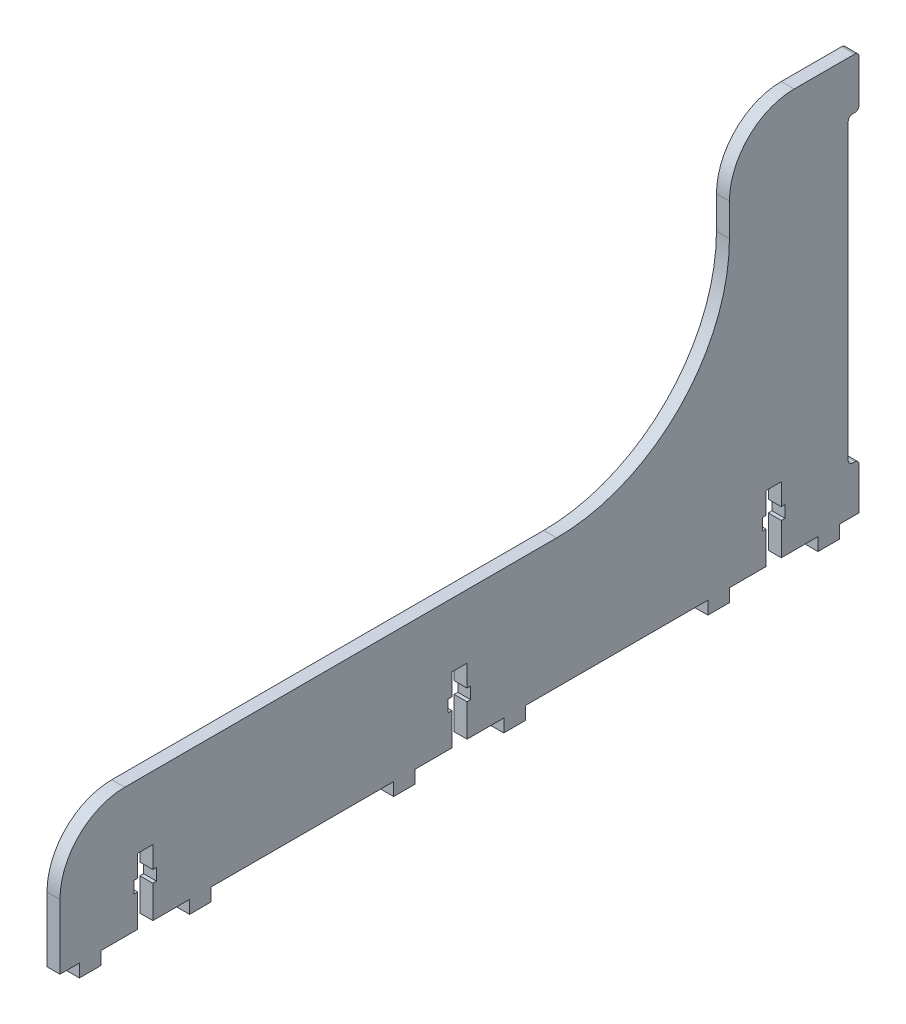
SolidWorks part; units mm, degrees
ref_plane "Front Plane" through (0, 0, 0) normal (0, 0, 1) x (1, 0, 0)
ref_plane "Top Plane" through (0, 0, 0) normal (0, 1, 0) x (1, 0, 0)
ref_plane "Right Plane" through (0, 0, 0) normal (1, 0, 0) x (0, 0, -1)
sketch "Sketch1" plane through (0, 0, 0) normal (1, 0, 0) x (0, 0, -1)
  line L0 (-185, -92.5) -> (185, 92.5) construction
  line L1 (183, 92.5) -> (155, 92.5)
  line L2 (-185, -92.5) -> (-185, -62.5)
  line L3 (-185, -92.5) -> (-176, -92.5)
  line L4 (185, -92.5) -> (185, -73)
  line L5 (0, -32.5) -> (0, -92.5) construction
  line L6 (149, -92.5) -> (149, -77.5)
  line L7 (149, -77.5) -> (150.7, -77.5)
  line L8 (150.7, -77.5) -> (150.7, -72)
  line L9 (150.7, -72) -> (149, -72)
  line L10 (149, -72) -> (149, -62)
  line L11 (149, -62) -> (142, -62)
  line L12 (142, -62) -> (142, -72)
  line L13 (142, -72) -> (140.3, -72)
  line L14 (140.3, -72) -> (140.3, -77.5)
  line L15 (140.3, -77.5) -> (142, -77.5)
  line L16 (142, -77.5) -> (142, -92.5)
  line L17 (166, -92.5) -> (166, -98.5)
  line L18 (166, -98.5) -> (176, -98.5)
  line L19 (176, -98.5) -> (176, -92.5)
  line L20 (115, -92.5) -> (115, -98.5)
  line L21 (115, -98.5) -> (125, -98.5)
  line L22 (125, -98.5) -> (125, -92.5)
  line L23 (30.5, -92.5) -> (30.5, -98.5)
  line L24 (30.5, -98.5) -> (20.5, -98.5)
  line L25 (20.5, -98.5) -> (20.5, -92.5)
  line L26 (-20.5, -92.5) -> (-20.5, -98.5)
  line L27 (-20.5, -98.5) -> (-30.5, -98.5)
  line L28 (-30.5, -98.5) -> (-30.5, -92.5)
  line L29 (-115, -92.5) -> (-115, -98.5)
  line L30 (-115, -98.5) -> (-125, -98.5)
  line L31 (-125, -98.5) -> (-125, -92.5)
  line L32 (-176, -92.5) -> (-176, -98.5)
  line L33 (-176, -98.5) -> (-166, -98.5)
  line L34 (-166, -98.5) -> (-166, -92.5)
  line L35 (166, -95.5) -> (125, -95.5) construction
  line L36 (115, -95.5) -> (30.5, -95.5) construction
  line L37 (20.5, -95.5) -> (-20.5, -95.5) construction
  line L38 (-30.5, -95.5) -> (-115, -95.5) construction
  line L39 (-125, -95.5) -> (-166, -95.5) construction
  line L40 (-166, -92.5) -> (-125, -92.5)
  line L41 (-115, -92.5) -> (-30.5, -92.5)
  line L42 (-20.5, -92.5) -> (20.5, -92.5)
  line L43 (30.5, -92.5) -> (115, -92.5)
  line L44 (125, -92.5) -> (166, -92.5)
  line L45 (145.5, -62) -> (145.5, -92.5) construction
  line L46 (176, -92.5) -> (185, -92.5)
  line L47 (72.75, -92.5) -> (72.75, -27.5329) construction
  line L48 (-3.5, -92.5) -> (-3.5, -77.5)
  line L49 (-3.5, -77.5) -> (-5.2, -77.5)
  line L50 (-5.2, -77.5) -> (-5.2, -72)
  line L51 (-5.2, -72) -> (-3.5, -72)
  line L52 (-3.5, -72) -> (-3.5, -62)
  line L53 (-3.5, -62) -> (3.5, -62)
  line L54 (3.5, -62) -> (3.5, -72)
  line L55 (3.5, -72) -> (5.2, -72)
  line L56 (5.2, -72) -> (5.2, -77.5)
  line L57 (5.2, -77.5) -> (3.5, -77.5)
  line L58 (3.5, -77.5) -> (3.5, -92.5)
  line L59 (-149, -92.5) -> (-149, -77.5)
  line L60 (-149, -77.5) -> (-150.7, -77.5)
  line L61 (-150.7, -77.5) -> (-150.7, -72)
  line L62 (-150.7, -72) -> (-149, -72)
  line L63 (-149, -72) -> (-149, -62)
  line L64 (-149, -62) -> (-142, -62)
  line L65 (-142, -62) -> (-142, -72)
  line L66 (-142, -72) -> (-140.3, -72)
  line L67 (-140.3, -72) -> (-140.3, -77.5)
  line L68 (-142, -77.5) -> (-142, -92.5)
  line L69 (-140.3, -77.5) -> (-142, -77.5)
  line L70 (183, -71) -> (182, -71)
  line L71 (-155, -32.5) -> (45, -32.5)
  line L72 (125, 47.5) -> (125, 62.5)
  line L73 (180, -69) -> (180, 67)
  line L74 (182, 69) -> (183, 69)
  line L75 (185, 71) -> (185, 90.5)
  arc A0 (125, 47.5) -> (45, -32.5) centre (45, 47.5) cw
  arc A1 (155, 92.5) -> (125, 62.5) centre (155, 62.5) ccw
  arc A2 (-155, -32.5) -> (-185, -62.5) centre (-155, -62.5) ccw
  arc A3 (185, 90.5) -> (183, 92.5) centre (183, 90.5) ccw
  arc A4 (185, 71) -> (183, 69) centre (183, 71) cw
  arc A5 (182, 69) -> (180, 67) centre (182, 67) ccw
  arc A6 (180, -69) -> (182, -71) centre (182, -69) ccw
  arc A7 (185, -73) -> (183, -71) centre (183, -73) ccw
  point P90 (-185, -32.5)
  point P94 (0, 0)
  point P95 (0, 0)
  point P96 (0, 0)
  point P104 (180, 69)
  point P107 (180, -71)
  point P110 (185, -71)
  dimension "D17" = 80
  dimension "D18" = 30
  dimension "D19" = 30
  dimension "D21" = 2
  dimension "D2" = 370
  dimension "D3" = 7
  dimension "D4" = 10
  dimension "D5" = 5.5
  dimension "D6" = 15
  dimension "D7" = 1.7
  dimension "D8" = 10
  dimension "D9" = 6
  dimension "D10" = 5
  dimension "D11" = 84.5
  dimension "D12" = 41
  dimension "D13" = 10.4
  dimension "D14" = 185
  dimension "D15" = 60
  dimension "D16" = 230
  dimension "D20" = 140
  dimension "D22" = 23.5
  dimension "D23" = 19.5
extrude "Boss-Extrude1" add sketch "Sketch1" along normal mid plane 6
